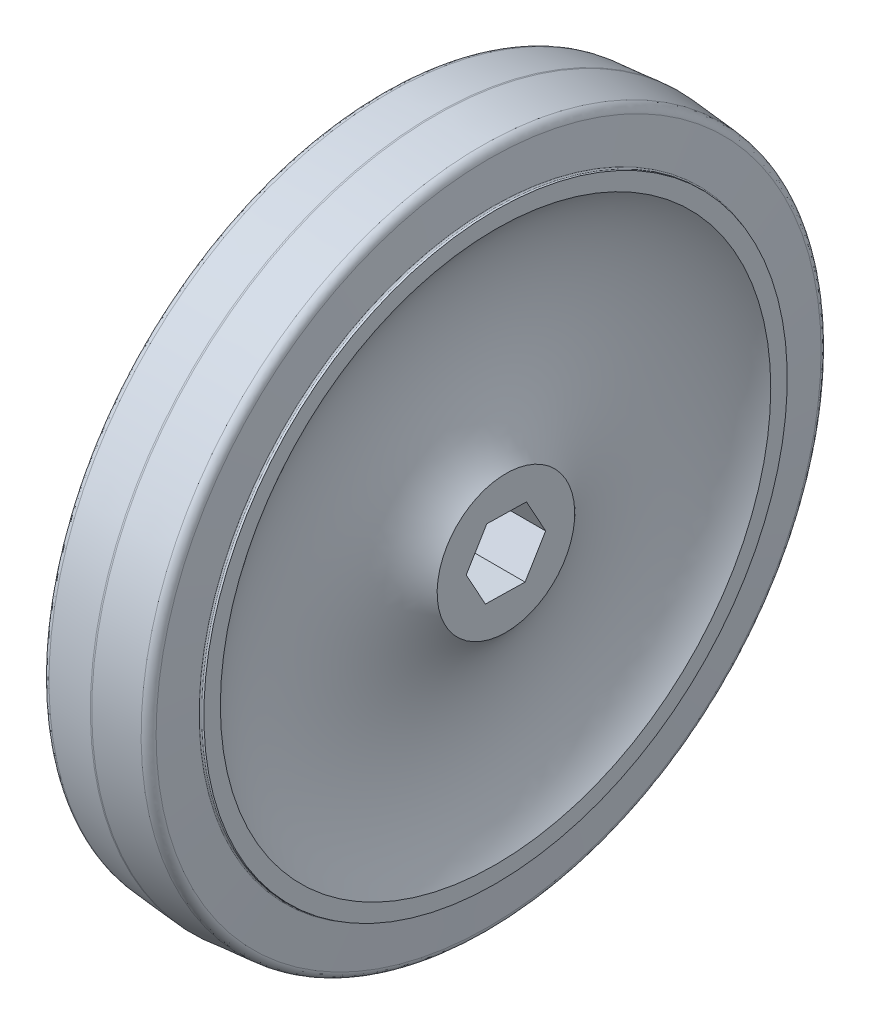
SolidWorks part; units mm, degrees
ref_plane "Front Plane" through (0, 0, 0) normal (0, 0, 1) x (1, 0, 0)
ref_plane "Top Plane" through (0, 0, 0) normal (0, 1, 0) x (1, 0, 0)
ref_plane "Right Plane" through (0, 0, 0) normal (1, 0, 0) x (0, 0, -1)
ref_plane "Plane1" through (0, 0, 0) normal (0, 0, -1) x (-1, 0, 0)
sketch "Sketch1" plane through (0, 0, 0) normal (0, 0, -1) x (-1, 0, 0)
  line L0 (-0.1328, 63.4884) -> (-8.5051, 62.7559)
  line L1 (-9.8905, 61.3705) -> (-10.5283, 54.0799)
  line L2 (-10.7813, 53.848) -> (-11.176, 53.848)
  line L3 (-11.176, 53.848) -> (-11.176, 50.8)
  line L4 (-13.0937, 12.7) -> (-13.0937, 7.6835)
  line L5 (-13.0937, 7.6835) -> (13.0937, 7.6835)
  line L6 (13.0937, 7.6835) -> (13.0937, 12.7)
  line L7 (11.176, 50.8) -> (11.176, 53.848)
  line L8 (11.176, 53.848) -> (10.7813, 53.848)
  line L9 (10.5283, 54.0799) -> (9.8905, 61.3705)
  line L10 (8.5051, 62.7559) -> (0.1328, 63.4884)
  line L11 (-14.7072, 0) -> (14.7072, 0) construction
  spline S0 degree 3 poles (-0.1328, 63.4884) (-0.0446, 63.4961) (0.0446, 63.4961) (0.1328, 63.4884) knots 0 0 0 0 1 1 1 1
  spline S1 degree 3 poles (-9.8905, 61.3705) (-9.8335, 62.0211) (-9.1557, 62.699) (-8.5051, 62.7559) knots 0 0 0 0 1 1 1 1
  spline S2 degree 3 poles (-10.5283, 54.0799) (-10.5383, 53.9659) (-10.6669, 53.848) (-10.7813, 53.848) knots 0 0 0 0 1 1 1 1
  spline S3 degree 3 poles (-11.176, 50.8) (-3.1892, 40.905) (-4.1537, 21.743) (-13.0937, 12.7) knots 0 0 0 0 1 1 1 1
  spline S4 degree 3 poles (13.0937, 12.7) (4.1537, 21.743) (3.1892, 40.905) (11.176, 50.8) knots 0 0 0 0 1 1 1 1
  spline S5 degree 3 poles (10.7813, 53.848) (10.6669, 53.848) (10.5383, 53.9659) (10.5283, 54.0799) knots 0 0 0 0 1 1 1 1
  spline S6 degree 3 poles (8.5051, 62.7559) (9.1557, 62.699) (9.8335, 62.0211) (9.8905, 61.3705) knots 0 0 0 0 1 1 1 1
revolve "Revolve1" add sketch "Sketch1" angle 360 about L11
sketch "Sketch2" plane through (13.0937, 0, 0) normal (1, 0, 0) x (0, 0, -1)
  line L1 (7.3308, -0.1489) -> (3.7943, 6.2743)
  line L2 (3.7943, 6.2743) -> (-3.5365, 6.4231)
  line L3 (-3.5365, 6.4231) -> (-7.3308, 0.1489)
  line L4 (-7.3308, 0.1489) -> (-3.7943, -6.2743)
  line L5 (-3.7943, -6.2743) -> (3.5365, -6.4231)
  line L6 (3.5365, -6.4231) -> (7.3308, -0.1489)
  circle A1 centre (0, 0) radius 6.35 construction
  circle A3 centre (0, 0) radius 7.6835
  circle A4 centre (0, 0) radius 7.6835
  dimension "D1" = 12.7
  dimension "D2" = 0
extrude "Boss-Extrude4" add sketch "Sketch2" against normal blind 26.1937
